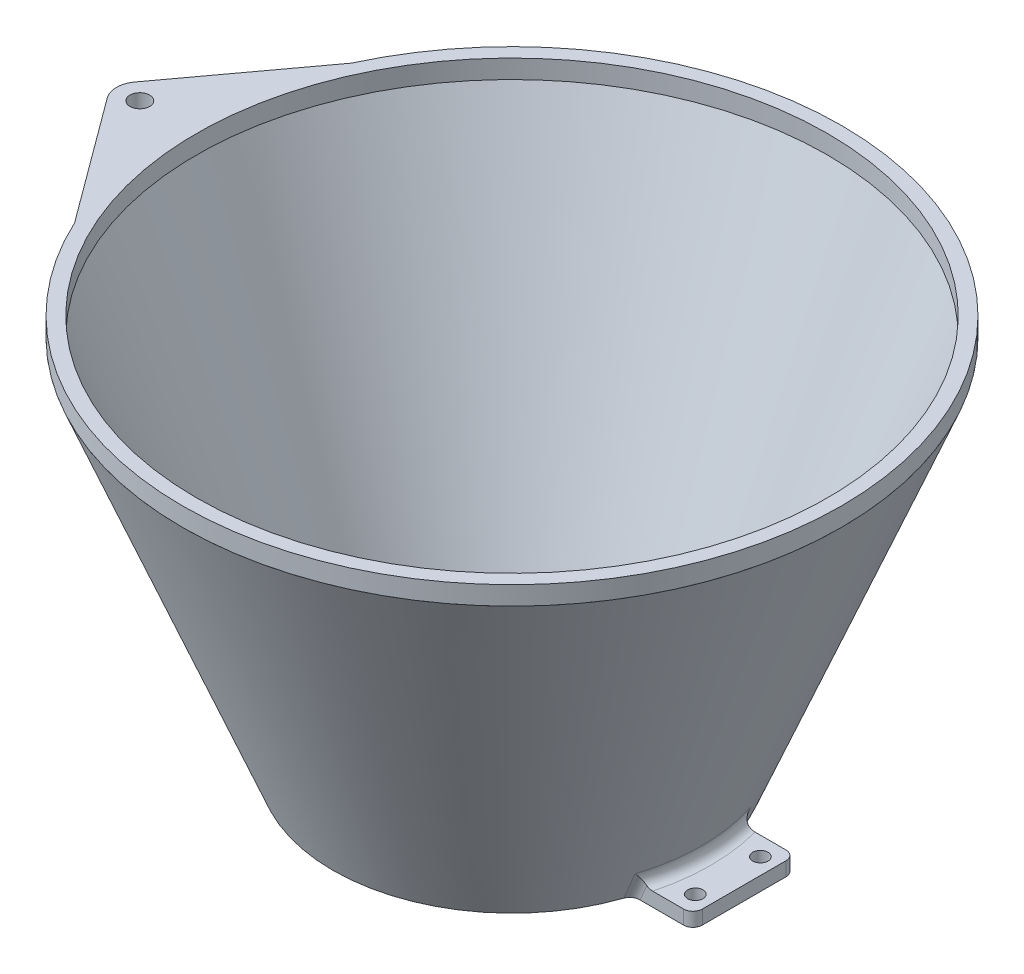
SolidWorks part; units mm, degrees
ref_plane "Front Plane" through (0, 0, 0) normal (0, 0, 1) x (1, 0, 0)
ref_plane "Top Plane" through (0, 0, 0) normal (0, 1, 0) x (1, 0, 0)
ref_plane "Right Plane" through (0, 0, 0) normal (1, 0, 0) x (0, 0, -1)
sketch "Sketch2" plane through (0, 0, 0) normal (0, 0, 1) x (1, 0, 0)
  line L0 (0, 0) -> (35.5, 0) construction
  line L1 (35.5, 0) -> (67.8221, 80)
  line L2 (35.5, 0) -> (38.5, 0) construction
  line L3 (38.5, 0) -> (70.8221, 80)
  line L4 (67.8221, 80) -> (70.8221, 80)
  line L5 (0, 0) -> (0, 42.1787) construction
  line L6 (35.5, 0) -> (38.5, 0)
  dimension "D1" = 35.5
  dimension "D2" = 38.5
  dimension "D3" = 80
  dimension "D4" = 112
  dimension "D5" = 80
  dimension "D6" = 0
revolve "Revolve1" add sketch "Sketch2" angle 360 about L5
sketch "Sketch3" plane through (0, 0, 0) normal (0, -1, 0) x (1, 0, 0)
  line L0 (-49.8951, 11) -> (-36.8951, 11)
  line L1 (-49.8951, 11) -> (-49.8951, -11)
  line L2 (-49.8951, -11) -> (-36.8951, -11)
  line L3 (-49.8951, 0) -> (0, 0) construction
  line L4 (0, 0) -> (0, 25.3337) construction
  line L5 (49.8951, -11) -> (36.8951, -11)
  line L6 (49.8951, 11) -> (49.8951, -11)
  line L7 (49.8951, 11) -> (36.8951, 11)
  circle A0 centre (0, 0) radius 38.5 construction
  circle A1 centre (0, 0) radius 38.5 construction
  circle A2 centre (-46.3951, -7) radius 1.65
  arc A3 (-36.8951, -11) -> (-36.8951, 11) centre (0, 0) cw
  circle A4 centre (-46.3951, 7) radius 1.65
  circle A5 centre (46.3951, 7) radius 1.65
  arc A6 (36.8951, -11) -> (36.8951, 11) centre (0, 0) ccw
  circle A7 centre (46.3951, -7) radius 1.65
  dimension "D2" = 3.3
  dimension "D1" = 22
  dimension "D3" = 7
  dimension "D4" = 3.5
  dimension "D5" = 13
extrude "Boss-Extrude1" add sketch "Sketch3" against normal blind 3
fillet "Fillet1" radius 2 10 edges at (49.8951, 1.5, -11) (49.8951, 1.5, 11) (-49.8951, 1.5, 11) (-49.8951, 1.5, -11) (39.7121, 3, 0) (-39.7121, 3, 0)
sketch "Sketch4" plane through (0, 80, 0) normal (0, 1, 0) x (1, 0, 0)
  line L0 (-80, 34.5374) -> (-80, -37.4895) construction
  line L1 (-108.9765, 0) -> (0, 0) construction
  line L7 (-84.0235, 2.9684) -> (-47.3766, 52.6424)
  line L8 (-84.0235, -2.9684) -> (-47.3766, -52.6424)
  line L11 (-95, 27) -> (-65, 27) construction
  line L12 (-65, -27) -> (-65, 27) construction
  line L13 (-95, -27) -> (-65, 27) construction
  line L14 (-95, 27) -> (-65, -27) construction
  circle A4 centre (0, 0) radius 70.8221 construction
  circle A6 centre (-80, 0) radius 2.125
  circle A8 centre (0, 0) radius 67.8221 construction
  circle A9 centre (0, 0) radius 67.8221
  arc A10 (-47.3766, -52.6424) -> (-47.3766, 52.6424) centre (0, 0) ccw
  arc A11 (-84.0235, 2.9684) -> (-84.0235, -2.9684) centre (-80, 0) ccw
  point P13 (-80, 0)
  point P16 (-80, 0)
  dimension "D10" = 4.25
  dimension "D2" = 10
  dimension "D4" = 80
  dimension "D7" = 54
  dimension "D8" = 30
extrude "Boss-Extrude2" add sketch "Sketch4" along normal blind 4 separate body
